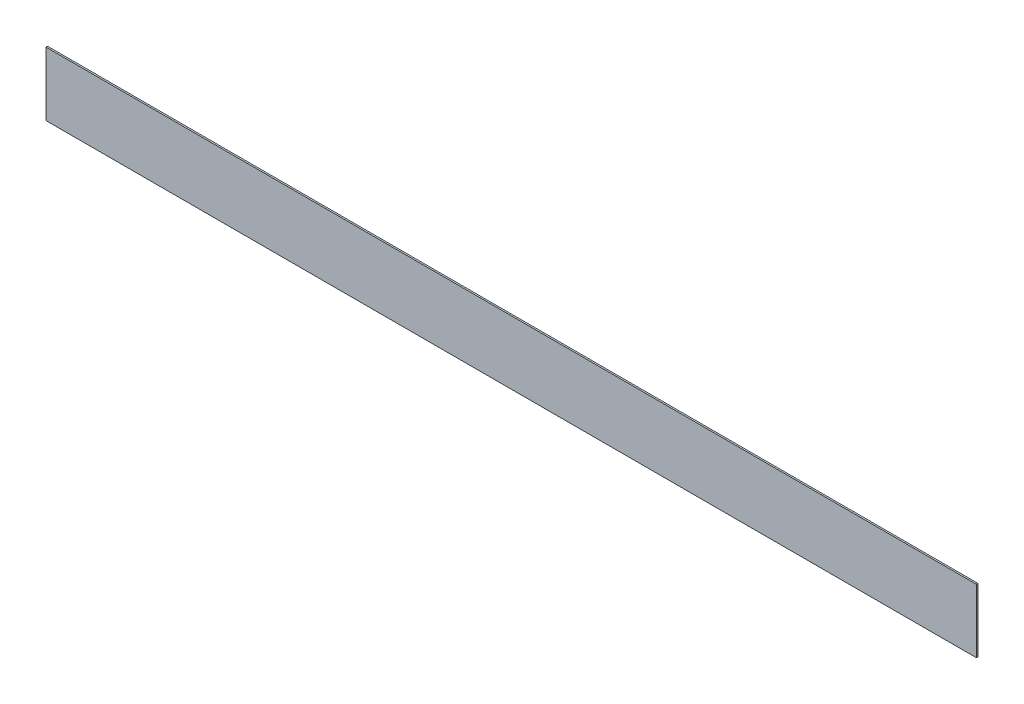
SolidWorks part; units mm, degrees
ref_plane "Front Plane" through (0, 0, 0) normal (0, 0, 1) x (1, 0, 0)
ref_plane "Top Plane" through (0, 0, 0) normal (0, 1, 0) x (1, 0, 0)
ref_plane "Right Plane" through (0, 0, 0) normal (1, 0, 0) x (0, 0, -1)
sketch "Sketch1" plane through (0, 0, 0) normal (0, 0, 1) x (1, 0, 0)
  line L1 (0, 0) -> (1170, 0)
  line L2 (0, 0) -> (0, -80)
  line L3 (0, -80) -> (1170, -80)
  line L4 (1170, 0) -> (1170, -80)
  dimension "D1" = 80
  dimension "D2" = 1170
extrude "Boss-Extrude1" add sketch "Sketch1" along normal blind 2
